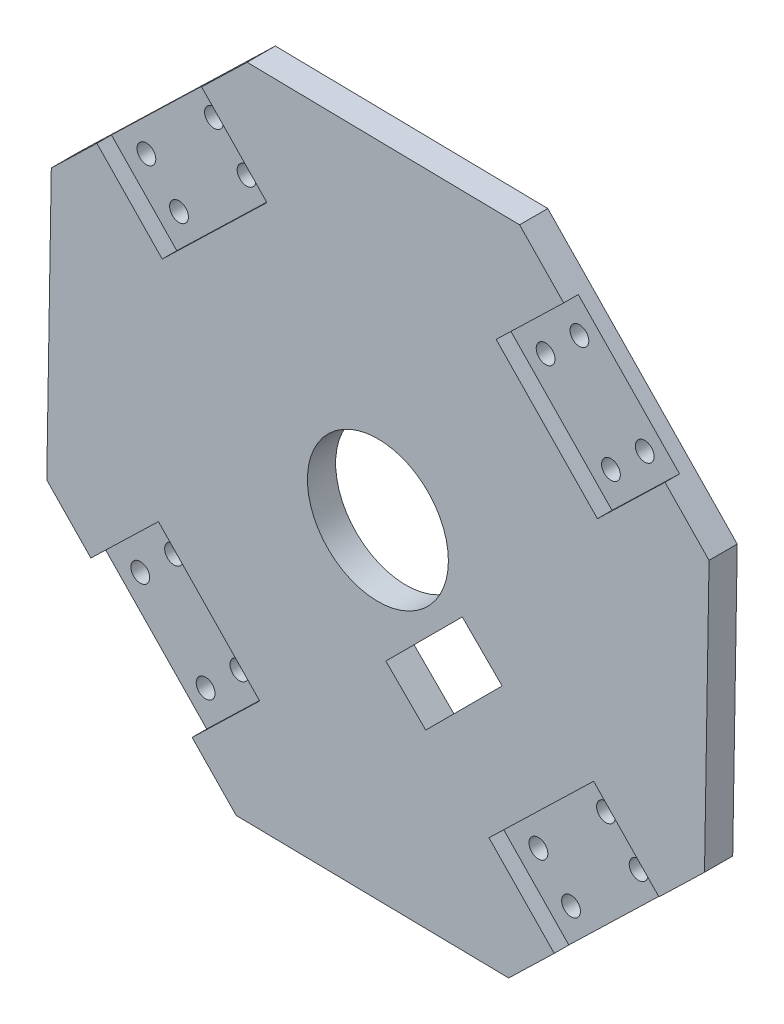
SolidWorks part; units mm, degrees
ref_plane "Plano frontal" through (0, 0, 0) normal (0, 0, 1) x (1, 0, 0)
ref_plane "Plano superior" through (0, 0, 0) normal (0, 1, 0) x (1, 0, 0)
ref_plane "Plano direito" through (0, 0, 0) normal (1, 0, 0) x (0, 0, -1)
sketch "Esboço2" plane through (0, 0, 0) normal (0, 0, 1) x (1, 0, 0)
  line L1 (70.4729, 27.8258) -> (30.1561, 69.5077)
  line L2 (30.1561, 69.5077) -> (-27.8258, 70.4729)
  line L3 (-27.8258, 70.4729) -> (-69.5077, 30.1561)
  line L4 (-69.5077, 30.1561) -> (-70.4729, -27.8258)
  line L5 (-70.4729, -27.8258) -> (-30.1561, -69.5077)
  line L6 (-30.1561, -69.5077) -> (27.8258, -70.4729)
  line L7 (27.8258, -70.4729) -> (69.5077, -30.1561)
  line L8 (69.5077, -30.1561) -> (70.4729, 27.8258)
  circle A0 centre (0, 0) radius 70 construction
  dimension "D1" = 140
  dimension "D2" = 140
extrude "Ressalto-extrusão1" add sketch "Esboço2" along normal blind 6 contours L3 L4 L5 L6 L7 L8 L1 L2
sketch "Esboço3" plane through (0, 0, 6) normal (0, 0, 1) x (1, 0, 0)
  line L0 (-61.0872, -37.5293) -> (-39.5348, -59.8114)
  line L1 (-70.4729, -27.8258) -> (-30.1561, -69.5077) construction
  line L2 (-39.5348, -59.8114) -> (-25.1592, -45.9066)
  line L3 (-25.1592, -45.9066) -> (-46.7116, -23.6245)
  line L4 (-46.7116, -23.6245) -> (-61.0872, -37.5293)
  line L5 (-48.6667, 50.3145) -> (48.6667, -50.3145) construction
  line L6 (-27.8258, 70.4729) -> (-69.5077, 30.1561) construction
  line L7 (27.8258, -70.4729) -> (69.5077, -30.1561) construction
  line L8 (46.7186, 23.6172) -> (25.1662, 45.8994)
  line L9 (61.0942, 37.522) -> (46.7186, 23.6172)
  line L10 (39.5418, 59.8042) -> (61.0942, 37.522)
  line L11 (25.1662, 45.8994) -> (39.5418, 59.8042)
  line L12 (-59.8042, 39.5418) -> (-37.522, 61.0942)
  line L13 (-37.522, 61.0942) -> (-23.6172, 46.7186)
  line L14 (-59.8042, 39.5418) -> (-45.8994, 25.1662)
  line L15 (-45.8994, 25.1662) -> (-23.6172, 46.7186)
  line L16 (-50.311, -48.6704) -> (50.318, 48.6631) construction
  line L17 (23.6315, -46.7189) -> (45.9137, -25.1665)
  line L18 (37.5363, -61.0945) -> (59.8184, -39.5421)
  line L19 (37.5363, -61.0945) -> (23.6315, -46.7189)
  line L20 (59.8184, -39.5421) -> (45.9137, -25.1665)
  dimension "D1" = 20
  dimension "D2" = 31
  dimension "D3" = 13.5
  dimension "D4" = 31
  dimension "D5" = 20
  dimension "D6" = 13.5
extrude "Corte-extrusão1" cut sketch "Esboço3" against normal blind 3.1
sketch "Esboço4" plane through (0, 0, 6) normal (0, 0, 1) x (1, 0, 0)
  circle A0 centre (0, 0) radius 15
  dimension "D1" = 30
extrude "Corte-extrusão2" cut sketch "Esboço4" against normal through all contours A0
sketch "Esboço6" plane through (0, 0, 2.9) normal (0, 0, 1) x (1, 0, 0)
  line L0 (-46.7116, -23.6245) -> (-61.0872, -37.5293) construction
  line L1 (-61.0872, -37.5293) -> (-39.5348, -59.8114) construction
  line L2 (-25.1592, -45.9066) -> (-46.7116, -23.6245) construction
  line L3 (23.6315, -46.7189) -> (37.5293, -61.0872) construction
  line L4 (59.8114, -39.5348) -> (37.5293, -61.0872) construction
  line L5 (45.9137, -25.1665) -> (23.6315, -46.7189) construction
  line L6 (59.8114, -39.5348) -> (45.9137, -25.1665) construction
  line L7 (0, 0) -> (50.318, 48.6631) construction
  line L8 (-39.5348, -59.8114) -> (-25.1592, -45.9066) construction
  line L9 (0, 0) -> (-48.6631, 50.318) construction
  line L10 (-37.522, 61.0942) -> (-59.8042, 39.5418) construction
  line L11 (61.0942, 37.522) -> (39.5418, 59.8042) construction
  circle A0 centre (-46.4817, -31.054) radius 2
  circle A1 centre (-53.6695, -38.0064) radius 2
  circle A4 centre (-39.7647, -52.3819) radius 2
  circle A5 centre (-32.5769, -45.4296) radius 2
  circle A6 centre (39.7793, 52.3689) radius 2
  circle A7 centre (32.5905, 45.4176) radius 2
  circle A8 centre (53.682, 37.9914) radius 2
  circle A9 centre (46.4932, 31.04) radius 2
  circle A10 centre (38.0064, -53.6695) radius 2
  circle A11 centre (31.061, -46.489) radius 2
  circle A12 centre (52.3819, -39.7647) radius 2
  circle A13 centre (45.4366, -32.5842) radius 2
  circle A14 centre (-37.9914, 53.682) radius 2
  circle A15 centre (-31.047, 46.5005) radius 2
  circle A16 centre (-45.4246, 32.5978) radius 2
  circle A17 centre (-52.3689, 39.7793) radius 2
  dimension "D2" = 4
  dimension "D3" = 4
  dimension "D4" = 5.5
  dimension "D9" = 5
  dimension "D8" = 4
  dimension "D11" = 5.5
  dimension "D7" = 4
  dimension "D12" = 5
  dimension "D13" = 4
  dimension "D14" = 4
  dimension "D15" = 4
  dimension "D16" = 4
  dimension "D17" = 5.5
  dimension "D19" = 5.5
  dimension "D20" = 5
  dimension "D21" = 5
  dimension "D22" = 5.5
  dimension "D24" = 5
  dimension "D1" = 5.5
  dimension "D5" = 5
  dimension "D6" = 5
  dimension "D10" = 5.5
  dimension "D18" = 5
  dimension "D23" = 5.5
extrude "Corte-extrusão3" cut sketch "Esboço6" against normal blind 3.1
sketch "Esboço7" plane through (0, 0, 6) normal (0, 0, 1) x (1, 0, 0)
  line L5 (10.1739, -33.6091) -> (1.6886, -25.1238)
  line L11 (17.9521, -8.8604) -> (26.4373, -17.3457)
  line L12 (26.4373, -17.3457) -> (10.1739, -33.6091)
  line L14 (1.6886, -25.1238) -> (17.9521, -8.8604)
  dimension "D1" = 23
  dimension "D2" = 12
extrude "Corte-extrusão7" cut sketch "Esboço7" against normal blind 10 contours L14 L11 L12 L5
